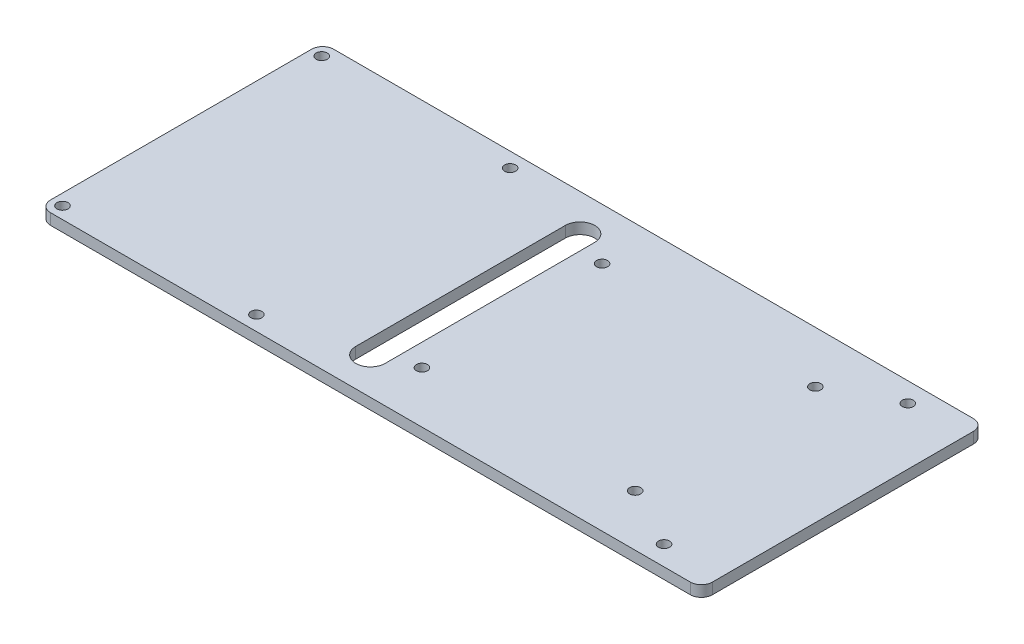
SolidWorks part; units mm, degrees
ref_plane "Front Plane" through (0, 0, 0) normal (0, 0, 1) x (1, 0, 0)
ref_plane "Top Plane" through (0, 0, 0) normal (0, 1, 0) x (1, 0, 0)
ref_plane "Right Plane" through (0, 0, 0) normal (1, 0, 0) x (0, 0, -1)
sketch "Sketch1" plane through (0, 0, 0) normal (0, 1, 0) x (1, 0, 0)
  line L0 (-90, 0) -> (0, 0) construction
  line L1 (-90, -38.5) -> (90, -38.5)
  line L2 (-90, -38.5) -> (-90, 38.5)
  line L3 (-90, 38.5) -> (90, 38.5)
  line L4 (90, -38.5) -> (90, 38.5)
  line L5 (-90, -38.5) -> (90, 38.5) construction
  line L6 (-90, 38.5) -> (90, -38.5) construction
  line L7 (-87, 35.25) -> (-34.7739, 35.25) construction
  line L8 (74.4946, 33.15) -> (74.4946, -33.15) construction
  line L9 (-87, 35.25) -> (-87, -35.25) construction
  circle A0 centre (-87, 35.25) radius 1.5
  circle A2 centre (-87, -35.25) radius 1.5
  circle A3 centre (-35.0054, 34.5) radius 1.5
  circle A4 centre (-35.0054, -34.5) radius 1.5
  circle A6 centre (74.4946, 33.15) radius 1.5007
  circle A7 centre (74.4946, -33.15) radius 1.5
  point P0 (0, 0)
  point P21 (74.4946, 0)
  dimension "D3" = 70.5
  dimension "D5" = 3
  dimension "D7" = 3
  dimension "D10" = 3.0015
  dimension "D14" = 3
  dimension "D1" = 180
  dimension "D2" = 66.3
  dimension "D4" = 77
  dimension "D6" = 52
  dimension "D8" = 109.5
  dimension "D9" = 3
extrude "Boss-Extrude1" add sketch "Sketch1" along normal blind 3
fillet "Fillet1" radius 3 4 edges at (-90, 1.5, -38.5) (-90, 1.5, 38.5) (90, 1.5, 38.5) (90, 1.5, -38.5)
sketch "Sketch2" plane through (0, 0, 0) normal (0, -1, 0) x (1, 0, 0)
  line L0 (90, 35.5) -> (90, -35.5) construction
  line L1 (-87, 38.5) -> (87, 38.5) construction
  line L3 (-14, 28.5) -> (-14, -28.5)
  line L4 (-6, -28.5) -> (-6, 28.5)
  circle A0 centre (58, 24.5) radius 1.5
  circle A1 centre (58, -24.5) radius 1.5
  circle A2 centre (0, -24.5) radius 1.5
  circle A3 centre (0, 24.5) radius 1.5
  arc A4 (-6, 28.5) -> (-14, 28.5) centre (-10, 28.5) ccw
  arc A5 (-14, -28.5) -> (-6, -28.5) centre (-10, -28.5) ccw
  dimension "D1" = 3
  dimension "D2" = 49
  dimension "D3" = 58
  dimension "D4" = 90
  dimension "D5" = 14
  dimension "D6" = 8
  dimension "D9" = 10
  dimension "D7" = 57
  dimension "D8" = 10
extrude "Cut-Extrude1" cut sketch "Sketch2" against normal up to surface (3 mm away) up to face at (0, 3, 0)
